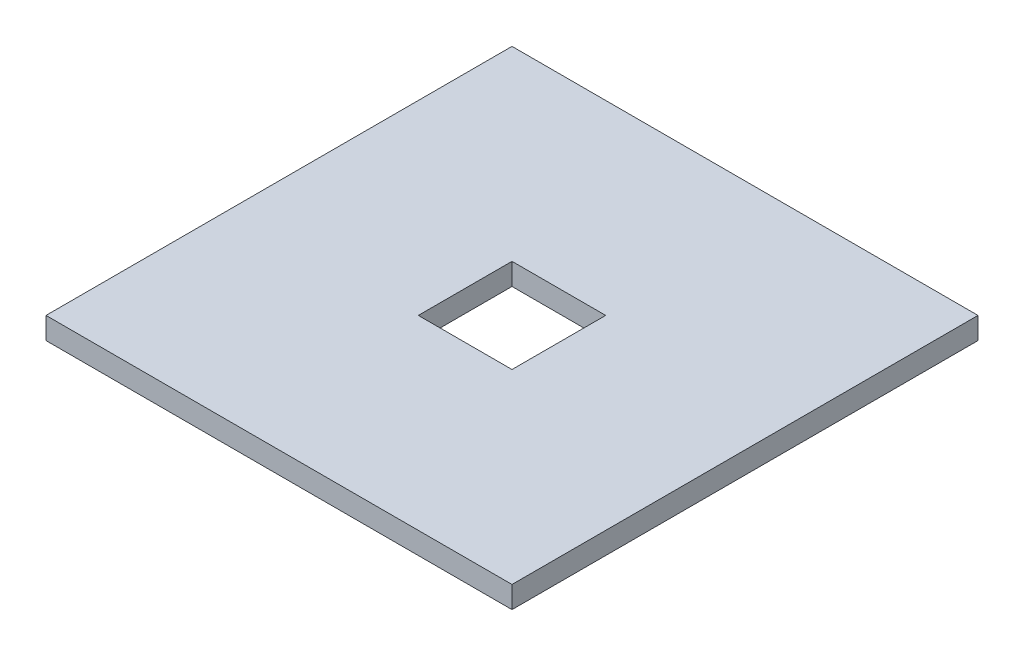
SolidWorks part; units mm, degrees
ref_plane "Front Plane" through (0, 0, 0) normal (0, 0, 1) x (1, 0, 0)
ref_plane "Top Plane" through (0, 0, 0) normal (0, 1, 0) x (1, 0, 0)
ref_plane "Right Plane" through (0, 0, 0) normal (1, 0, 0) x (0, 0, -1)
sketch "Sketch1" plane through (0, 0, 0) normal (0, 1, 0) x (1, 0, 0)
  line L1 (-149.225, -149.225) -> (149.225, -149.225)
  line L2 (-149.225, -149.225) -> (-149.225, 149.225)
  line L3 (-149.225, 149.225) -> (149.225, 149.225)
  line L4 (149.225, -149.225) -> (149.225, 149.225)
  line L5 (-149.225, -149.225) -> (149.225, 149.225) construction
  line L6 (-149.225, 149.225) -> (149.225, -149.225) construction
  point P0 (0, 0)
  dimension "D1" = 298.45
  dimension "D2" = 298.45
extrude "Boss-Extrude1" add sketch "Sketch1" along normal blind 13.97
sketch "Sketch3" plane through (0, 13.97, 0) normal (0, 1, 0) x (1, 0, 0)
  line L1 (-30, -30) -> (30, -30)
  line L2 (-30, -30) -> (-30, 30)
  line L3 (-30, 30) -> (30, 30)
  line L4 (30, -30) -> (30, 30)
  line L5 (-30, -30) -> (30, 30) construction
  line L6 (-30, 30) -> (30, -30) construction
  point P0 (0, 0)
  dimension "D1" = 60
extrude "Cut-Extrude2" cut sketch "Sketch3" against normal through all
